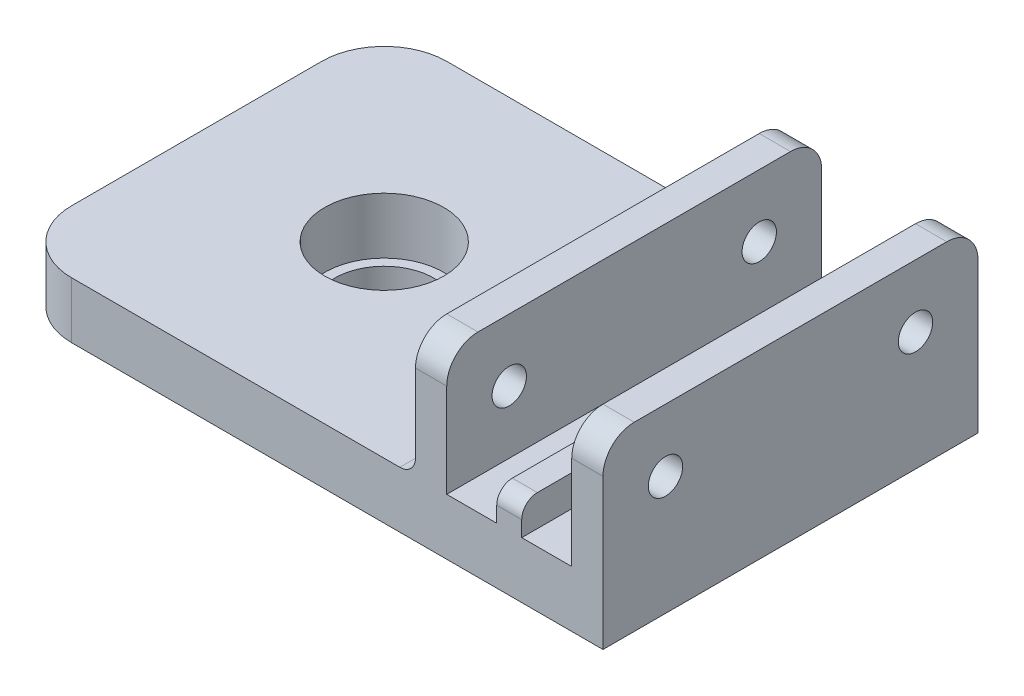
SolidWorks part; units mm, degrees
ref_plane "Front" through (0, 0, 0) normal (0, 0, 1) x (1, 0, 0)
ref_plane "Top" through (0, 0, 0) normal (0, 1, 0) x (1, 0, 0)
ref_plane "Right" through (0, 0, 0) normal (1, 0, 0) x (0, 0, -1)
sketch "Sketch1" plane through (0, 0, 0) normal (0, 1, 0) x (1, 0, 0)
  line L0 (65, 30) -> (65, -30)
  line L1 (-30, -30) -> (65, -30)
  line L2 (-30, -30) -> (-30, 30)
  line L3 (-30, 30) -> (65, 30)
  line L5 (0, -50) -> (0, 50) construction
  line L6 (-50, 0) -> (50, 0) construction
  point P0 (0, 0)
  point P8 (-30, 0)
  dimension "D1" = 60
  dimension "D2" = 95
  dimension "D3" = 30
extrude "Boss-Extrude1" add sketch "Sketch1" along normal blind 9 contours L3 L0 L1 L2
sketch "Sketch5" plane through (0, 0, 0) normal (0, -1, 0) x (1, 0, 0)
  circle A0 centre (0, 0) radius 17.5
  dimension "D1" = 35
extrude "Boss-Extrude2" add sketch "Sketch5" along normal blind 10
sketch "Sketch6" plane through (0, 9, 0) normal (0, 1, 0) x (1, 0, 0)
  circle A0 centre (0, 0) radius 7.9375
  dimension "D1" = 15.875
extrude "Cut-Extrude1" cut sketch "Sketch6" against normal blind 14
sketch "Sketch8" plane through (0, 9, 0) normal (0, 1, 0) x (1, 0, 0)
  circle A0 centre (0, 0) radius 9.525
  dimension "D1" = 19.05
extrude "Cut-Extrude2" cut sketch "Sketch8" against normal blind 9
sketch "Sketch9" plane through (0, -10, 0) normal (0, -1, 0) x (1, 0, 0)
  circle A0 centre (0, 0) radius 3.5
  dimension "D1" = 7
extrude "Cut-Extrude3" cut sketch "Sketch9" against normal up to next contours A0
sketch "Sketch10" plane through (0, 0, 0) normal (0, 0, 1) x (1, 0, 0)
  line L0 (-30, 9) -> (65, 9) construction
  line L1 (65, 9) -> (60, 9)
  line L2 (65, 9) -> (65, 29)
  line L3 (65, 29) -> (60, 29)
  line L4 (60, 9) -> (60, 29)
  line L5 (35, 29) -> (40, 29)
  line L6 (35, 29) -> (35, 9)
  line L7 (35, 9) -> (40, 9)
  line L8 (40, 29) -> (40, 9)
  line L10 (48, 14) -> (52, 14)
  line L11 (48, 14) -> (48, 9)
  line L12 (48, 9) -> (52, 9)
  line L13 (52, 14) -> (52, 9)
  point P15 (50, 14)
  dimension "D1" = 5
  dimension "D2" = 20
  dimension "D3" = 20
  dimension "D4" = 10
  dimension "D5" = 4
  dimension "D6" = 5
extrude "Boss-Extrude3" add sketch "Sketch10" along direction (0, 0, -1) on the side of the normal up to surface (60 mm away) from surface at -30
sketch "Sketch11" plane through (65, 0, 0) normal (1, 0, 0) x (0, 0, -1)
  line L0 (-30, 29) -> (30, 29) construction
  line L1 (-30, 29) -> (-30, 0) construction
  point P0 (-20, 19)
  dimension "D1" = 10
  dimension "D2" = 10
hole_wizard "M5 Clearance Hole1" positions "Sketch12" profile "Sketch14" hole size "M5" standard "ANSI Metric" end condition through all
sketch "Sketch12" plane through (65, 0, 0) normal (1, 0, 0) x (0, 0, -1)
  point P0 (-20, 19)
sketch "Sketch14" plane through (65, 19, 20) normal (0, 1, 0) x (0, 0, -1)
  line L0 (0, 0) -> (0, 95)
  line L1 (0, 95) -> (2.75, 95)
  line L2 (2.75, 95) -> (2.75, 0)
  line L5 (2.75, 0) -> (0, 0)
  line L11 (0, -6.35) -> (0, 107.95) construction
  dimension "Thru Hole Dia." = 5.5
  dimension "Thru Hole Depth" = 95
mirror "Mirror1" about plane through (0, 0, 0) normal (0, 0, 1) of "M5 Clearance Hole1"
fillet "Fillet1" radius 5 4 edges at (62.5, 29, 30) (62.5, 29, -30) (37.5, 29, 30) (37.5, 29, -30)
fillet "Fillet2" radius 2.5 2 edges at (50, 14, 30) (50, 14, -30)
fillet "Fillet3" radius 10 2 edges at (-30, 4.5, 30) (-30, 4.5, -30)
fillet "Fillet4" radius 2.5 1 edges at (35, 9, 0)
hole_wizard "CBORE for M5 SBHCS1" positions "Sketch2" profile "Sketch4" counterbore size "M5" standard "ANSI Metric"
sketch "Sketch2" plane through (0, 0, 0) normal (0, -1, 0) x (-1, 0, 0)
  point P0 (0, 0)
sketch "Sketch4" plane through (0, 0, 0) normal (1, 0, 0) x (0, 0, -1)
  line L0 (0, 0) -> (0, 7)
  line L1 (0, 7) -> (2.75, 7)
  line L3 (2.75, 7) -> (2.75, 5.08)
  line L4 (2.75, 5.08) -> (7.9375, 5.08)
  line L5 (7.9375, 5.08) -> (7.9375, 0)
  line L7 (7.9375, 0) -> (0, 0)
  line L11 (0, -6.35) -> (0, 107.95) construction
  dimension "Thru Hole Dia." = 5.5
  dimension "Thru Hole Depth" = 7
  dimension "C'Bore Dia." = 15.875
  dimension "C'Bore Depth" = 5.08
